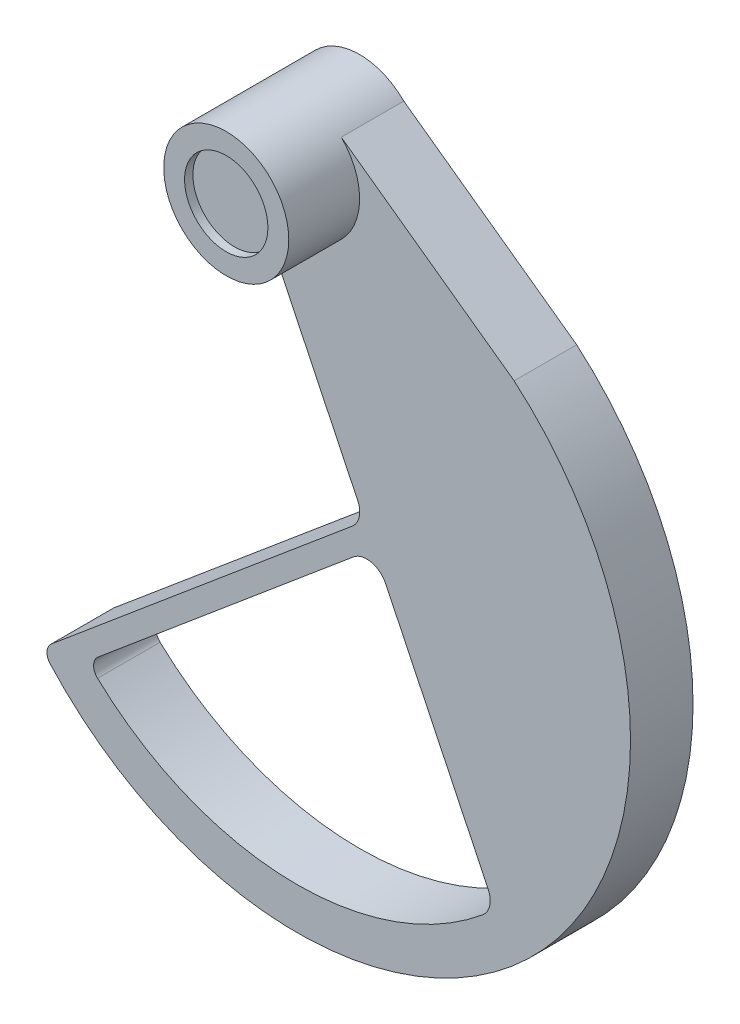
SolidWorks part; units mm, degrees
ref_plane "正面" through (0, 0, 0) normal (0, 0, 1) x (1, 0, 0)
ref_plane "平面" through (0, 0, 0) normal (0, 1, 0) x (1, 0, 0)
ref_plane "右側面" through (0, 0, 0) normal (1, 0, 0) x (0, 0, -1)
sketch "ｽｹｯﾁ4" plane through (0, 0, 0) normal (0, 0, 1) x (1, 0, 0)
  line L0 (0, 0.7897) -> (0, 0)
  line L1 (-53.6231, -124.9951) -> (-58.9406, -129.4571)
  line L3 (-10.6066, -10.6066) -> (14.5363, -62.8896)
  line L4 (-53.6231, -124.9951) -> (13.2442, -68.8868)
  line L5 (21.2324, -76.8138) -> (45.8448, -127.9938)
  line L6 (10.6066, 10.6066) -> (52.0762, -19.2705)
  line L7 (-58.0696, -135.2532) -> (-57.9498, -135.1527)
  line L8 (-47.7477, -126.5866) -> (13.5112, -75.1515)
  arc A1 (-59.2335, -133.7716) -> (52.0762, -19.2705) centre (0, -80) ccw
  arc A2 (-47.8702, -131.073) -> (44.5187, -134.0193) centre (0, -80) ccw
  arc A3 (10.6066, 10.6066) -> (-10.6066, -10.6066) centre (0, 0) ccw
  arc A4 (-59.2335, -133.7716) -> (-58.9406, -129.4571) centre (-57.0123, -131.7552) cw
  arc A5 (-47.8702, -131.073) -> (-47.7477, -126.5866) centre (-45.8186, -128.8841) cw
  arc A6 (13.5112, -75.1515) -> (21.2324, -76.8138) centre (16.7264, -78.9807) cw
  arc A7 (13.2442, -68.8868) -> (14.5363, -62.8896) centre (10.0302, -65.0566) ccw
  arc A8 (45.8448, -127.9938) -> (44.5187, -134.0193) centre (41.3388, -130.1608) cw
  point P18 (-61.2836, -131.423)
  point P21 (-50.2744, -128.7081)
  point P24 (18.4421, -71.0114)
  dimension "D3" = 140
  dimension "D4" = 30
  dimension "D5" = 5
  dimension "D6" = 3
  dimension "D7" = 3
  dimension "D8" = 5
  dimension "D9" = 5
  dimension "D10" = 5
  dimension "D2" = 5
extrude "ﾎﾞｽ - 押し出し1" add sketch "ｽｹｯﾁ4" along normal blind 15
sketch "ｽｹｯﾁ5" plane through (0, 0, 15) normal (0, 0, 1) x (1, 0, 0)
  circle A0 centre (0, 0) radius 15
  dimension "D1" = 30
extrude "ﾎﾞｽ - 押し出し2" add sketch "ｽｹｯﾁ5" along normal blind 17
sketch "ｽｹｯﾁ7" plane through (0, 0, 32) normal (0, 0, 1) x (1, 0, 0)
  circle A0 centre (0, 0) radius 10
  dimension "D1" = 20
extrude "ｶｯﾄ - 押し出し1" cut sketch "ｽｹｯﾁ7" against normal blind 2
